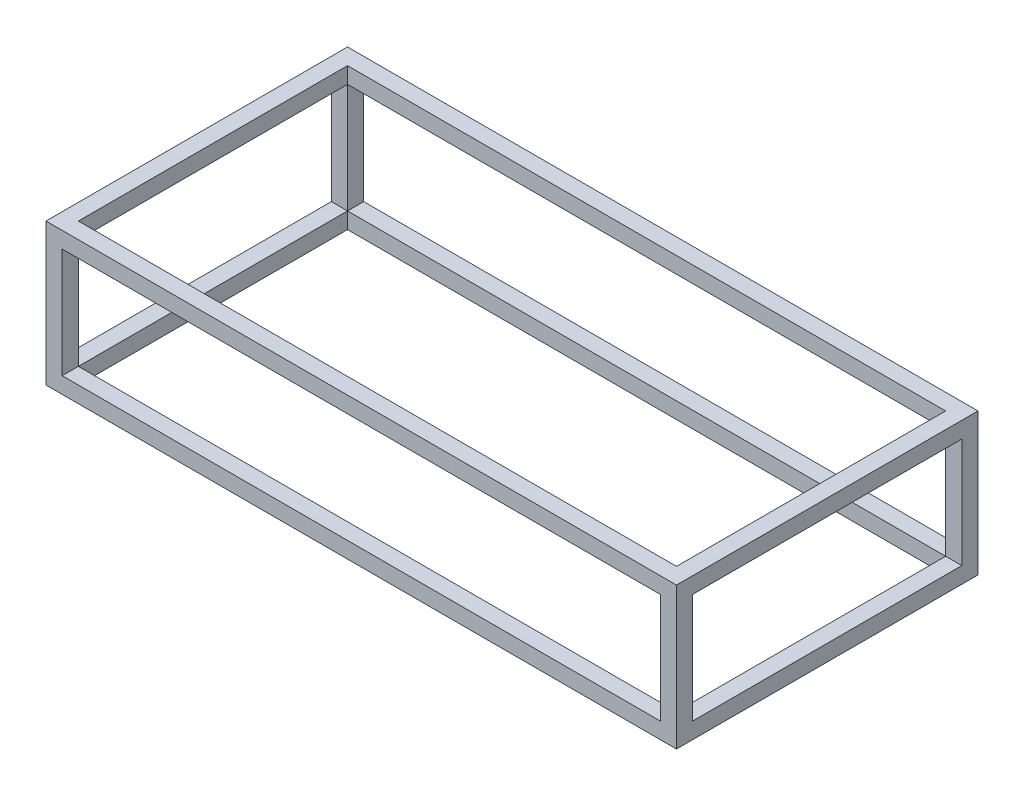
SolidWorks part; units mm, degrees
ref_plane "Front Plane" through (0, 0, 0) normal (0, 0, 1) x (1, 0, 0)
ref_plane "Top Plane" through (0, 0, 0) normal (0, 1, 0) x (1, 0, 0)
ref_plane "Right Plane" through (0, 0, 0) normal (1, 0, 0) x (0, 0, -1)
sketch "Sketch3" plane through (0, 0, 0) normal (0, 1, 0) x (1, 0, 0)
  line L1 (-277.1, 124.7) -> (277.1, 124.7)
  line L2 (-277.1, 124.7) -> (-277.1, -124.7)
  line L3 (-277.1, -124.7) -> (277.1, -124.7)
  line L4 (277.1, 124.7) -> (277.1, -124.7)
  line L5 (-277.1, 124.7) -> (277.1, -124.7) construction
  line L6 (-277.1, -124.7) -> (277.1, 124.7) construction
  line L7 (-292.1, 139.7) -> (292.1, 139.7)
  line L8 (-292.1, 139.7) -> (-292.1, -139.7)
  line L9 (-292.1, -139.7) -> (292.1, -139.7)
  line L10 (292.1, 139.7) -> (292.1, -139.7)
  line L11 (-292.1, 139.7) -> (292.1, -139.7) construction
  line L12 (-292.1, -139.7) -> (292.1, 139.7) construction
  point P0 (0, 0)
  point P6 (0, 0)
  dimension "D1" = 584.2
  dimension "D2" = 15
  dimension "D3" = 15
  dimension "D4" = 279.4
extrude "Boss-Extrude3" add sketch "Sketch3" along normal blind 15
sketch "Sketch4" plane through (0, 15, 0) normal (0, 1, 0) x (1, 0, 0)
  line L0 (-277.1, -124.7) -> (277.1, -124.7) construction
  line L1 (-292.1, 139.7) -> (-277.1, 139.7)
  line L2 (-292.1, 139.7) -> (-292.1, 124.7)
  line L3 (-292.1, 124.7) -> (-277.1, 124.7)
  line L4 (-277.1, 139.7) -> (-277.1, 124.7)
  line L5 (-292.1, -139.7) -> (-277.1, -139.7)
  line L6 (-292.1, -139.7) -> (-292.1, -124.7)
  line L7 (-292.1, -124.7) -> (-277.1, -124.7)
  line L8 (-277.1, -139.7) -> (-277.1, -124.7)
  line L9 (292.1, -139.7) -> (277.1, -139.7)
  line L10 (292.1, -139.7) -> (292.1, -124.7)
  line L11 (292.1, -124.7) -> (277.1, -124.7)
  line L12 (277.1, -139.7) -> (277.1, -124.7)
  line L14 (292.1, 139.7) -> (277.1, 139.7)
  line L15 (292.1, 139.7) -> (292.1, 124.7)
  line L16 (292.1, 124.7) -> (277.1, 124.7)
  line L17 (277.1, 139.7) -> (277.1, 124.7)
extrude "Boss-Extrude4" add sketch "Sketch4" along normal blind 101.6
sketch "Sketch5" plane through (0, 116.6, 0) normal (0, 1, 0) x (1, 0, 0)
  line L1 (-292.1, 139.7) -> (292.1, 139.7)
  line L2 (-292.1, 139.7) -> (-292.1, -139.7)
  line L3 (-292.1, -139.7) -> (292.1, -139.7)
  line L4 (292.1, 139.7) -> (292.1, -139.7)
  line L5 (-277.1, 124.7) -> (277.1, 124.7)
  line L6 (-277.1, 124.7) -> (-277.1, -124.7)
  line L7 (-277.1, -124.7) -> (277.1, -124.7)
  line L8 (277.1, 124.7) -> (277.1, -124.7)
extrude "Boss-Extrude6" add sketch "Sketch5" along normal blind 15
